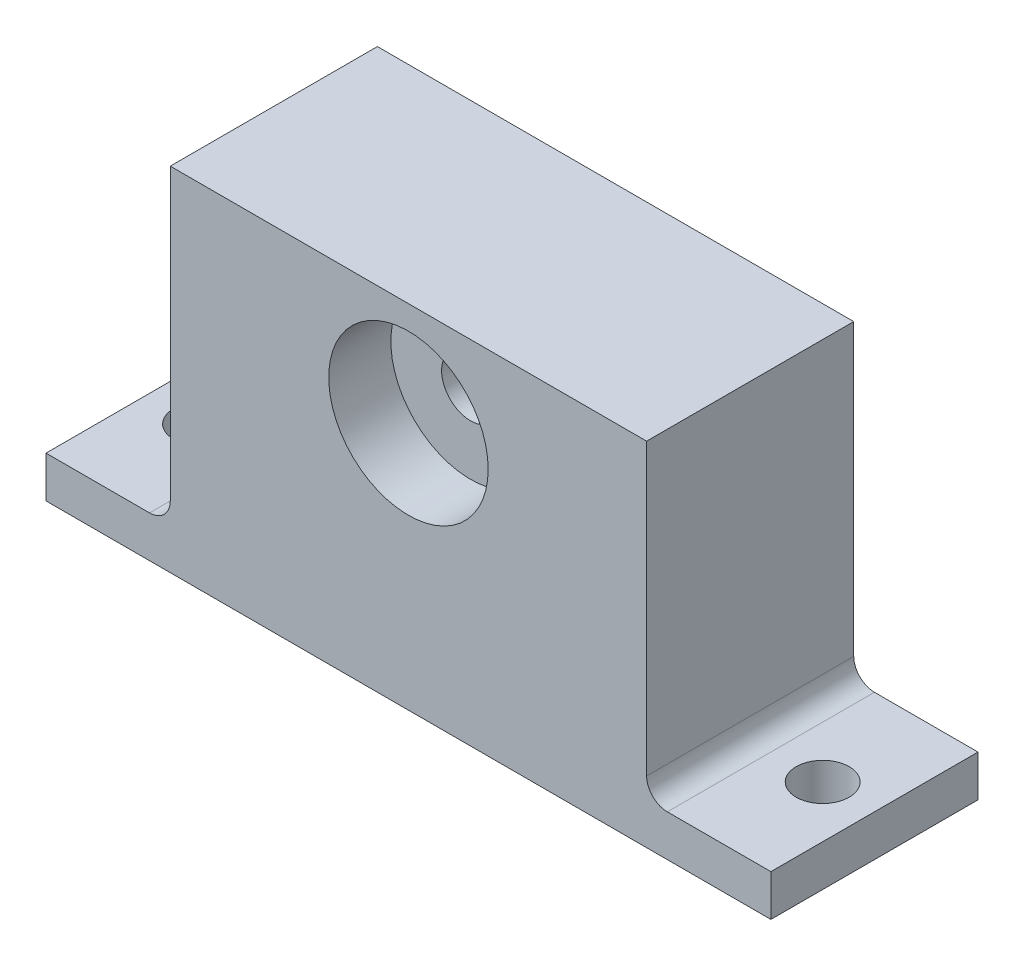
SolidWorks part; units mm, degrees
material "ABS"
ref_plane "Front Plane" through (0, 0, 0) normal (0, 0, 1) x (1, 0, 0)
ref_plane "Top Plane" through (0, 0, 0) normal (0, 1, 0) x (1, 0, 0)
ref_plane "Right Plane" through (0, 0, 0) normal (1, 0, 0) x (0, 0, -1)
sketch "Sketch1" plane through (0, 0, 0) normal (0, 0, 1) x (1, 0, 0)
  line L1 (-22.225, -10.795) -> (22.225, -10.795)
  line L2 (-22.225, -10.795) -> (-22.225, 10.795)
  line L3 (-22.225, 10.795) -> (22.225, 10.795)
  line L4 (22.225, -10.795) -> (22.225, 10.795)
  line L5 (-22.225, -10.795) -> (22.225, 10.795) construction
  line L6 (-22.225, 10.795) -> (22.225, -10.795) construction
  point P0 (0, 0)
  dimension "D1" = 44.45
  dimension "D2" = 21.59
extrude "Boss-Extrude1" add sketch "Sketch1" along normal blind 12.7
sketch "Sketch2" plane through (0, 0, 12.7) normal (0, 0, 1) x (1, 0, 0)
  line L0 (-22.225, -10.795) -> (22.225, -10.795) construction
  line L1 (-22.225, 10.795) -> (-14.605, 10.795)
  line L2 (-22.225, 10.795) -> (-22.225, -8.255)
  line L3 (-22.225, -8.255) -> (-14.605, -8.255)
  line L4 (-14.605, 10.795) -> (-14.605, -8.255)
  line L5 (22.225, 10.795) -> (14.605, 10.795)
  line L6 (22.225, 10.795) -> (22.225, -8.255)
  line L7 (22.225, -8.255) -> (14.605, -8.255)
  line L8 (14.605, 10.795) -> (14.605, -8.255)
  dimension "D1" = 7.62
  dimension "D2" = 7.62
  dimension "D3" = 2.54
  dimension "D4" = 2.54
extrude "Cut-Extrude1" cut sketch "Sketch2" against normal blind 12.7
fillet "Fillet1" radius 1.27 1 edges at (-14.605, -8.255, 6.35)
fillet "Fillet2" radius 1.27 1 edges at (14.605, -8.255, 6.35)
sketch "Sketch4" plane through (0, -8.255, 0) normal (0, 1, 0) x (1, 0, 0)
  line L0 (22.225, 0) -> (22.225, -12.7) construction
  line L1 (15.875, 0) -> (22.225, 0) construction
  line L2 (-22.225, 0) -> (-15.875, 0) construction
  line L3 (-22.225, 0) -> (-22.225, -12.7) construction
  circle A0 centre (19.05, -6.35) radius 1.6256
  circle A1 centre (-19.05, -6.4262) radius 1.6256
  dimension "D1" = 3.2512
  dimension "D2" = 3.2512
  dimension "D3" = 3.175
  dimension "D4" = 6.35
  dimension "D5" = 6.4262
  dimension "D6" = 3.175
extrude "Cut-Extrude3" cut sketch "Sketch4" against normal blind 12.7
sketch "Sketch5" plane through (0, 0, 0) normal (0, 0, -1) x (-1, 0, 0)
  line L0 (-14.605, 10.795) -> (14.605, 10.795) construction
  circle A0 centre (0, 4.445) radius 1.778
  dimension "D1" = 3.556
  dimension "D2" = 6.35
extrude "Cut-Extrude4" cut sketch "Sketch5" against normal blind 12.7
sketch "Sketch6" plane through (0, 0, 12.7) normal (0, 0, 1) x (1, 0, 0)
  circle A0 centre (0, 4.445) radius 4.8895
  dimension "D1" = 9.779
extrude "Cut-Extrude5" cut sketch "Sketch6" against normal blind 3.81
